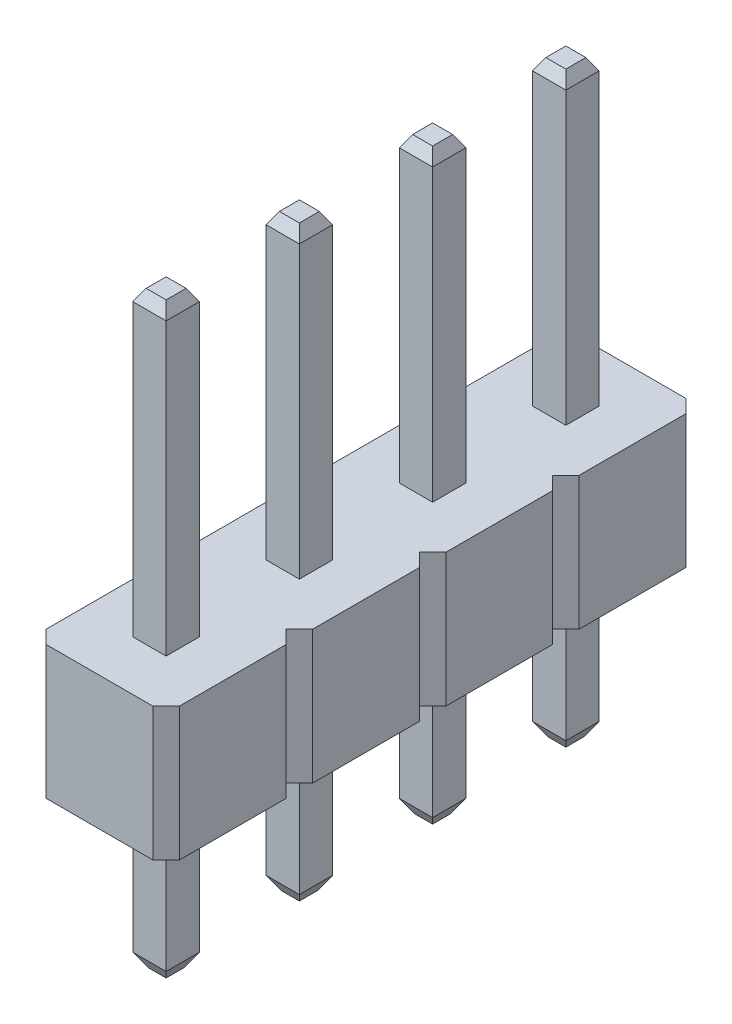
SolidWorks part; units mm, degrees
ref_plane "Front Plane" through (0, 0, 0) normal (0, 0, 1) x (1, 0, 0)
ref_plane "Top Plane" through (0, 0, 0) normal (0, 1, 0) x (1, 0, 0)
ref_plane "Right Plane" through (0, 0, 0) normal (1, 0, 0) x (0, 0, -1)
sketch "Sketch1" plane through (0, 0, 0) normal (0, 1, 0) x (1, 0, 0)
  line L0 (1.016, 1.27) -> (1.27, 1.016)
  line L1 (-1.016, -1.27) -> (1.016, -1.27)
  line L2 (-1.27, -1.016) -> (-1.27, 1.016)
  line L3 (-1.016, 1.27) -> (1.016, 1.27)
  line L4 (1.27, -1.016) -> (1.27, 1.016)
  line L5 (-1.27, -1.27) -> (1.27, 1.27) construction
  line L6 (-1.27, 1.27) -> (1.27, -1.27) construction
  line L7 (1.016, -1.27) -> (1.27, -1.016)
  line L8 (-1.27, -1.016) -> (-1.016, -1.27)
  line L9 (-1.27, 1.016) -> (-1.016, 1.27)
  point P0 (0, 0)
  dimension "D1" = 2.54
  dimension "D2" = 2.54
extrude "Boss-Extrude1" add sketch "Sketch1" along normal blind 2.54
sketch "Sketch2" plane through (0, 0, 0) normal (0, 0, 1) x (1, 0, 0)
  line L0 (0, 0) -> (0, -2.921)
  line L1 (0, 0) -> (0, 8.2931)
  point P9 (0, 4.318)
  dimension "D1" = 11.2141
  dimension "D3" = 2.921
ref_plane "Plane1" through (0, -2.921, 0) normal (0, -1, 0) x (-1, 0, 0)
sketch "Sketch3" plane through (0, -2.921, 0) normal (0, -1, 0) x (-1, 0, 0)
  line L1 (0.3175, 0.3175) -> (-0.3175, 0.3175)
  line L2 (0.3175, 0.3175) -> (0.3175, -0.3175)
  line L3 (0.3175, -0.3175) -> (-0.3175, -0.3175)
  line L4 (-0.3175, 0.3175) -> (-0.3175, -0.3175)
  line L5 (0.3175, 0.3175) -> (-0.3175, -0.3175) construction
  line L6 (0.3175, -0.3175) -> (-0.3175, 0.3175) construction
  point P0 (0, 0)
  dimension "D1" = 0.635
  dimension "D2" = 0.635
sweep "Sweep1" add profiles "Sketch3" path "Sketch2"
chamfer "Chamfer1" distance 0.254 angle 30 4 edges at (0, -2.921, -0.3175) (-0.3175, -2.921, 0) (0, -2.921, 0.3175) (0.3175, -2.921, 0)
chamfer "Chamfer2" distance 0.127 angle 60 4 edges at (0, 8.2931, 0.3175) (-0.3175, 8.2931, 0) (0, 8.2931, -0.3175) (0.3175, 8.2931, 0)
pattern_linear "LPattern1" count 4 spacing 2.54 along (0, 0, 1) of "Boss-Extrude1", "Chamfer1", "Chamfer2", "Sweep1"
ref_plane "Plane2" through (0, 0, 3.81) normal (0, 0, 1) x (1, 0, 0)
